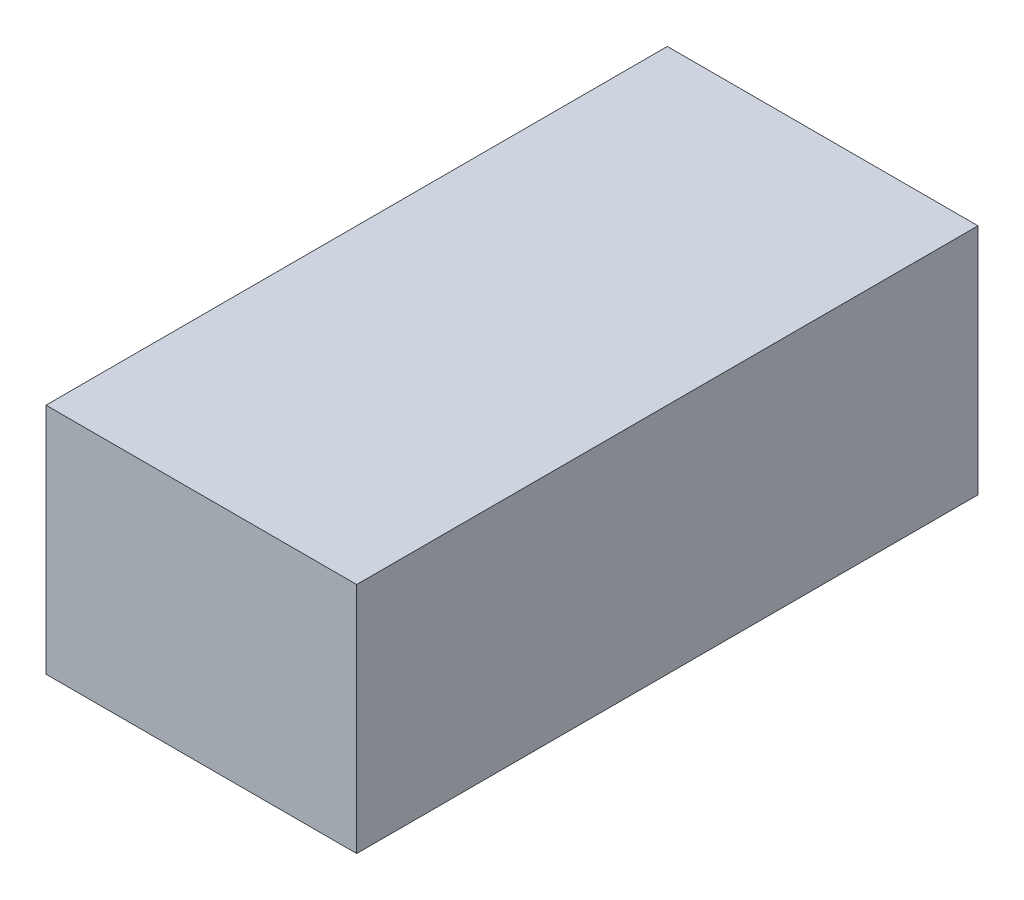
SolidWorks part; units mm, degrees
ref_plane "Front Plane" through (0, 0, 0) normal (0, 0, 1) x (1, 0, 0)
ref_plane "Top Plane" through (0, 0, 0) normal (0, 1, 0) x (1, 0, 0)
ref_plane "Right Plane" through (0, 0, 0) normal (1, 0, 0) x (0, 0, -1)
sketch "Sketch1" plane through (0, 0, 0) normal (0, 1, 0) x (1, 0, 0)
  line L1 (-50, 100) -> (50, 100)
  line L2 (-50, 100) -> (-50, -100)
  line L3 (-50, -100) -> (50, -100)
  line L4 (50, 100) -> (50, -100)
  line L5 (-50, 100) -> (50, -100) construction
  line L6 (-50, -100) -> (50, 100) construction
  point P0 (0, 0)
  dimension "D1" = 100
  dimension "D2" = 200
extrude "Boss-Extrude1" add sketch "Sketch1" along normal blind 75
